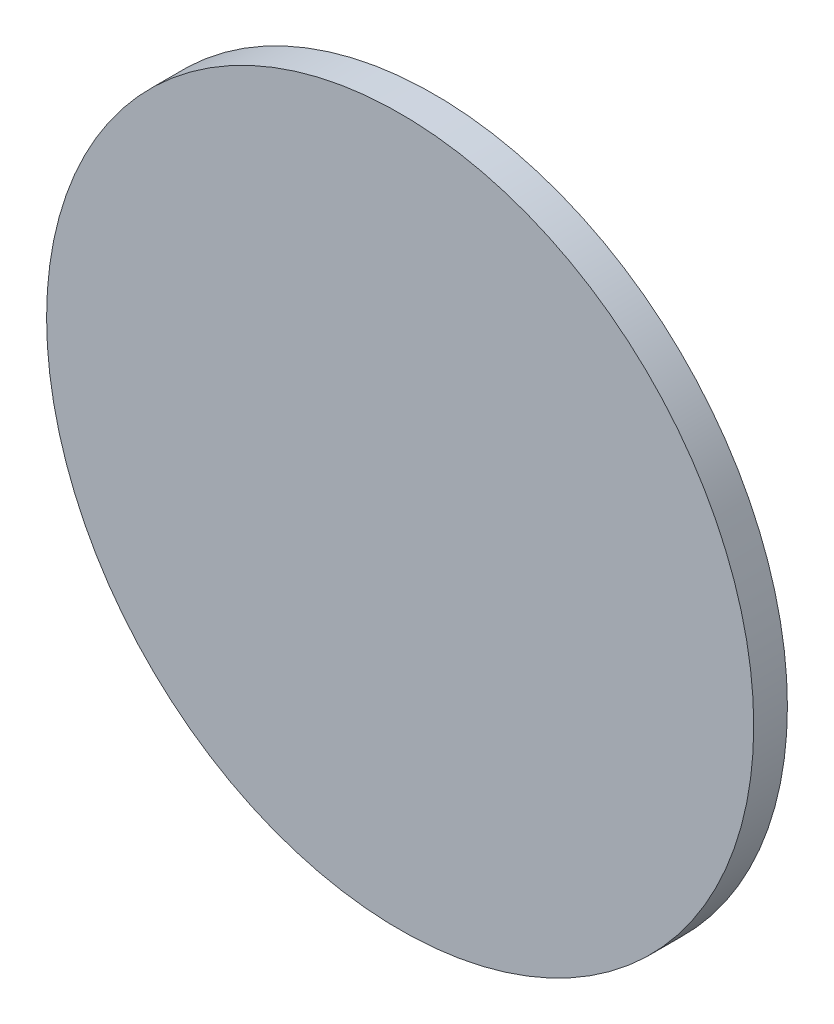
SolidWorks part; units mm, degrees
material "AISI 304"
ref_plane "Спереди" through (0, 0, 0) normal (0, 0, 1) x (1, 0, 0)
ref_plane "Сверху" through (0, 0, 0) normal (0, 1, 0) x (1, 0, 0)
ref_plane "Справа" through (0, 0, 0) normal (1, 0, 0) x (0, 0, -1)
other "Configuration Table"
sketch "Эскиз1" plane through (0, 0, 0) normal (0, 0, 1) x (1, 0, 0)
  circle A0 centre (0, 0) radius 21
  dimension "D1" = 42
extrude "Бобышка-Вытянуть1" add sketch "Эскиз1" along normal blind 2
move or copy body "Тело-Переместить/Копировать2" [suppressed] bodies to move or copy 103 parameters "D1"=0, "D2"=0, "D3"=0
move or copy body "Тело-Переместить/Копировать1" [suppressed] bodies to move or copy 103 parameters "D1"=0, "D2"=0, "D3"=0
